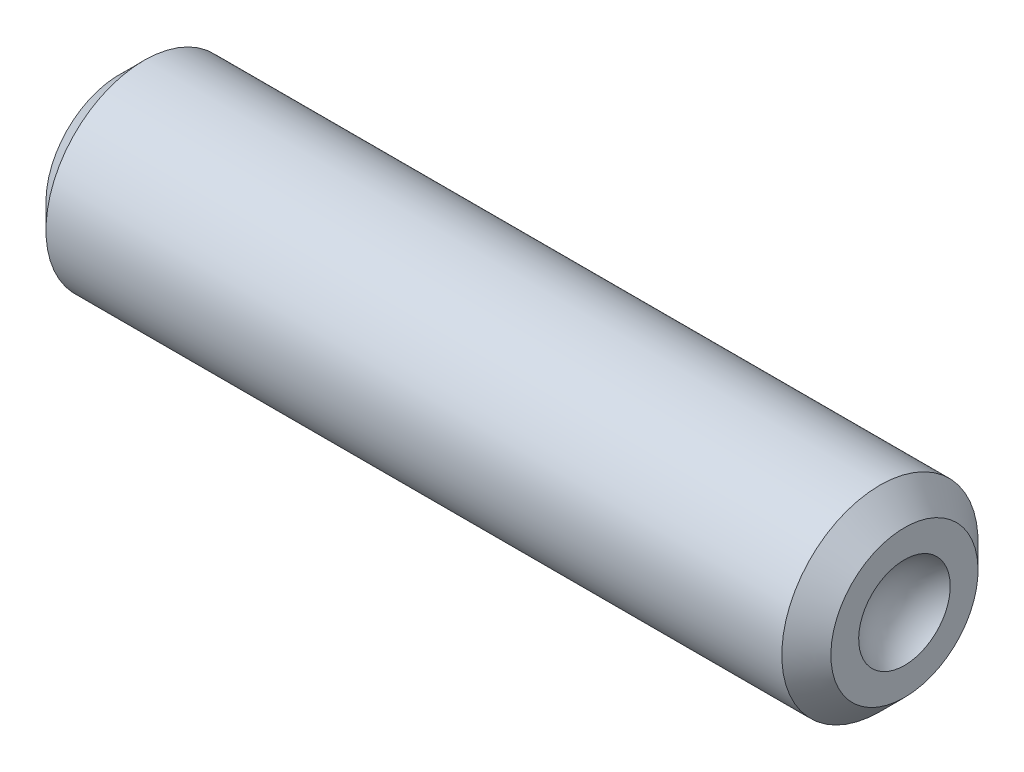
SolidWorks part; units mm, degrees
ref_plane "Front Plane" through (0, 0, 0) normal (0, 0, 1) x (1, 0, 0)
ref_plane "Top Plane" through (0, 0, 0) normal (0, 1, 0) x (1, 0, 0)
ref_plane "Right Plane" through (0, 0, 0) normal (1, 0, 0) x (0, 0, -1)
sketch "Sketch1" plane through (0, 0, 0) normal (0, 0, 1) x (1, 0, 0)
  line L0 (0, 0) -> (0, 1.125)
  line L1 (0, 1.125) -> (0.375, 1.5)
  line L2 (0.375, 1.5) -> (11.625, 1.5)
  line L3 (11.625, 1.5) -> (12, 1.125)
  line L4 (0, 0) -> (11.625, 0) construction
  line L5 (0.375, 1.5) -> (0.375, 1.125) construction
  line L6 (0.375, 1.125) -> (0.375, 0.75) construction
  line L7 (0.375, 0.75) -> (0.375, 0.375) construction
  line L8 (0.375, 0.375) -> (0.375, 0) construction
  line L9 (0.375, 1.125) -> (0, 1.125) construction
  line L10 (11.625, 1.5) -> (11.625, 0) construction
  line L11 (12, 1.125) -> (12, 0.7)
  line L12 (0, 0) -> (11.625, 0)
  arc A0 (11.625, 0) -> (12, 0.7) centre (12.4658, 0) cw
  dimension "D1" = 45
  dimension "D2" = 3
  dimension "D3" = 12
  dimension "D4" = 1.4
revolve "Revolve1" add sketch "Sketch1" angle 360 about L12
sketch "Sketch2" plane through (0, 0, 0) normal (-1, 0, 0) x (0, 0, 1)
  line L1 (0, 0.866) -> (-0.75, 0.433)
  line L2 (-0.75, 0.433) -> (-0.75, -0.433)
  line L3 (-0.75, -0.433) -> (0, -0.866)
  line L4 (0, -0.866) -> (0.75, -0.433)
  line L5 (0.75, -0.433) -> (0.75, 0.433)
  line L6 (0.75, 0.433) -> (0, 0.866)
  circle A0 centre (0, 0) radius 0.75 construction
  dimension "D1" = 1.5
extrude "Cut-Extrude1" cut sketch "Sketch2" against normal offset from surface (10 mm away) 2 up to face at (12, -1.125, 0)
